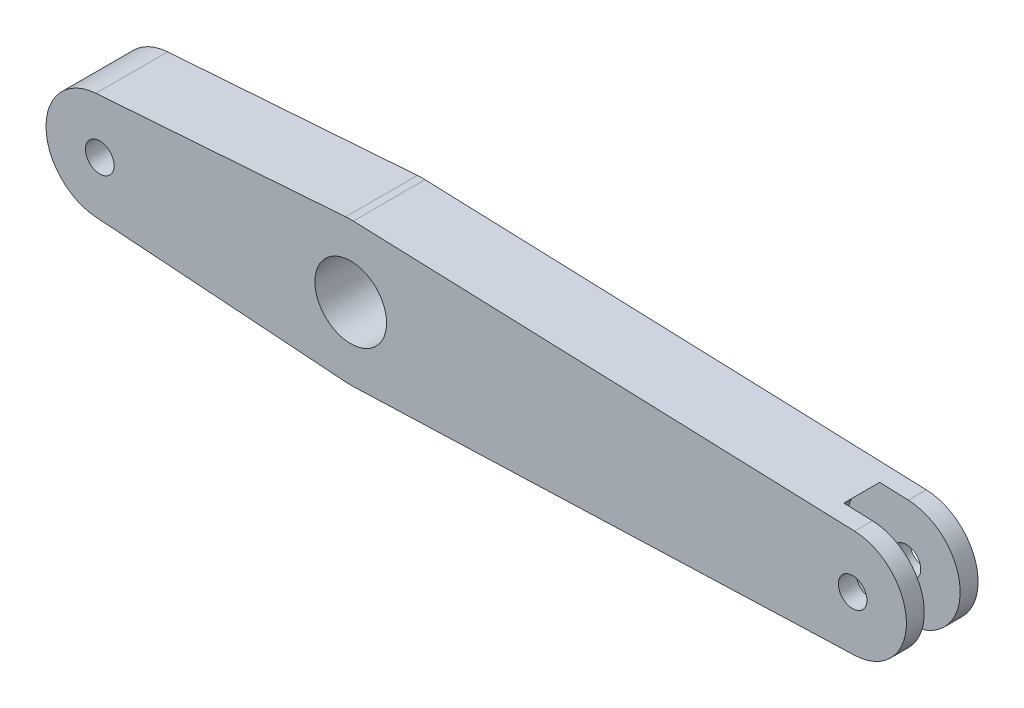
SolidWorks part; units mm, degrees
ref_plane "前视基准面" through (0, 0, 0) normal (0, 0, 1) x (1, 0, 0)
ref_plane "上视基准面" through (0, 0, 0) normal (0, 1, 0) x (1, 0, 0)
ref_plane "右视基准面" through (0, 0, 0) normal (1, 0, 0) x (0, 0, -1)
other "Configuration Table"
sketch "草图1" plane through (0, 0, 0) normal (0, 0, 1) x (1, 0, 0)
  line L0 (-71.0714, 14.9617) -> (-1.4286, 19.9489)
  line L1 (-71.0714, -14.9617) -> (-1.4286, -19.9489)
  line L2 (140.5357, 14.9904) -> (0.7143, 19.9872)
  line L3 (140.5357, -14.9904) -> (0.7143, -19.9872)
  arc A0 (-1.4286, -19.9489) -> (0.7143, -19.9872) centre (0, 0) ccw
  arc A1 (-71.0714, 14.9617) -> (-71.0714, -14.9617) centre (-70, 0) ccw
  arc A2 (140.5357, -14.9904) -> (140.5357, 14.9904) centre (140, 0) ccw
  arc A3 (0.7143, 19.9872) -> (-1.4286, 19.9489) centre (0, 0) ccw
  circle A4 centre (0, 0) radius 10
  circle A5 centre (-70, 0) radius 4
  circle A6 centre (140, 0) radius 4
extrude "凸台-拉伸1" add sketch "草图1" along normal blind 20
sketch "草图2" plane through (0, 0, 0) normal (0, 0, 1) x (1, 0, 0)
  circle A0 centre (140, 0) radius 17
extrude "切除-拉伸1" cut sketch "草图2" along normal blind 10 from offset 5
